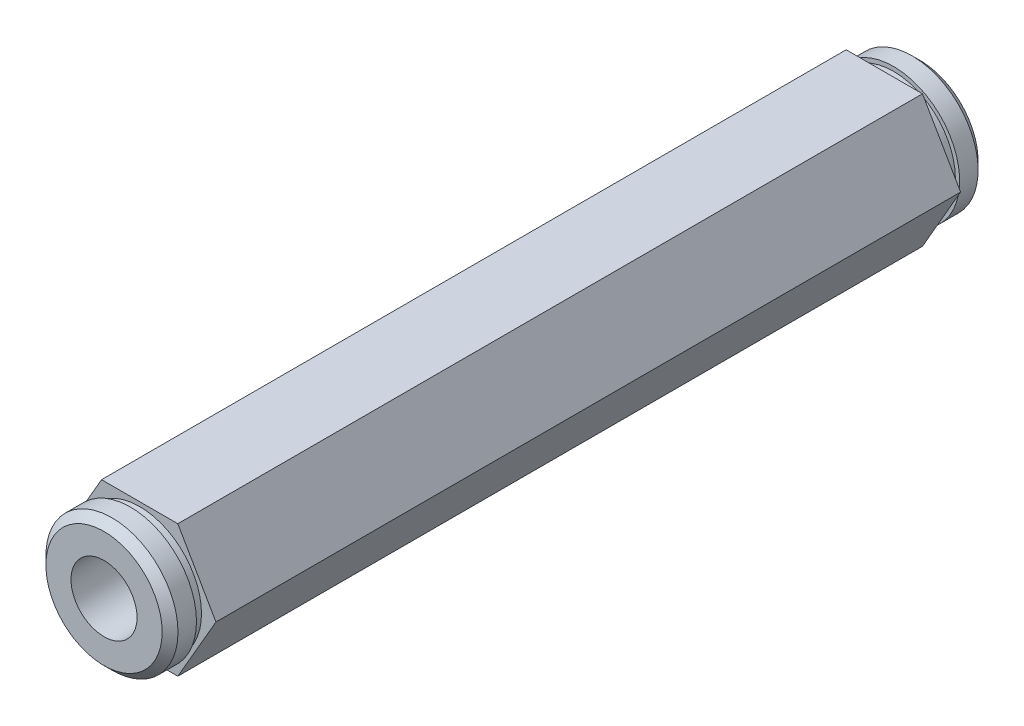
SolidWorks part; units mm, degrees
ref_plane "Front Plane" through (0, 0, 0) normal (0, 0, 1) x (1, 0, 0)
ref_plane "Top Plane" through (0, 0, 0) normal (0, 1, 0) x (1, 0, 0)
ref_plane "Right Plane" through (0, 0, 0) normal (1, 0, 0) x (0, 0, -1)
sketch "Sketch1" plane through (0, 0, 0) normal (0, 0, 1) x (1, 0, 0)
  line L1 (7.3323, 0) -> (3.6662, 6.35)
  line L2 (3.6662, 6.35) -> (-3.6662, 6.35)
  line L3 (-3.6662, 6.35) -> (-7.3323, 0)
  line L4 (-7.3323, 0) -> (-3.6662, -6.35)
  line L5 (-3.6662, -6.35) -> (3.6662, -6.35)
  line L6 (3.6662, -6.35) -> (7.3323, 0)
  circle A0 centre (0, 0) radius 6.35 construction
  dimension "D1" = 12.7
extrude "Boss-Extrude1" add sketch "Sketch1" along normal mid plane 28.575
sketch "Sketch2" plane through (0, 0, -14.2875) normal (0, 0, -1) x (-1, 0, 0)
  circle A0 centre (0, 0) radius 5.9436
  dimension "D1" = 11.8872
extrude "Boss-Extrude2" add sketch "Sketch2" along normal blind 0.889
sketch "Sketch3" plane through (0, 0, -15.1765) normal (0, 0, -1) x (-1, 0, 0)
  circle A0 centre (0, 0) radius 6.35
  dimension "D1" = 12.7
extrude "Boss-Extrude3" add sketch "Sketch3" along normal blind 2.54
chamfer "Chamfer1" distance 0.762 angle 45 1 edges at (-6.35, 0, -17.7165)
sketch "Sketch5" plane through (0, 0, 14.2875) normal (0, 0, 1) x (1, 0, 0)
  line L1 (3.6662, 6.35) -> (-3.6662, 6.35)
  line L2 (-3.6662, 6.35) -> (-7.3323, 0)
  line L3 (-7.3323, 0) -> (-3.6662, -6.35)
  line L4 (-3.6662, -6.35) -> (3.6662, -6.35)
  line L5 (3.6662, -6.35) -> (7.3323, 0)
  line L6 (7.3323, 0) -> (3.6662, 6.35)
  circle A0 centre (0, 0) radius 6.35 construction
  dimension "D1" = 12.7
extrude "Boss-Extrude4" add sketch "Sketch5" along normal blind 43.0149
sketch "Sketch6" plane through (0, 0, 57.3024) normal (0, 0, 1) x (1, 0, 0)
  circle A0 centre (0, 0) radius 5.9436
  dimension "D1" = 11.8872
extrude "Boss-Extrude5" add sketch "Sketch6" along normal blind 0.889
sketch "Sketch7" plane through (0, 0, 58.1914) normal (0, 0, 1) x (1, 0, 0)
  circle A0 centre (0, 0) radius 6.35
  dimension "D1" = 12.7
extrude "Boss-Extrude6" add sketch "Sketch7" along normal blind 2.54
chamfer "Chamfer2" distance 0.762 angle 45 1 edges at (6.35, 0, 60.7314)
hole_wizard "1/4 (0.25) Diameter Hole1" positions "Sketch10" profile "Sketch11" hole size "1/4" standard "ANSI Inch"
sketch "Sketch10" plane through (0, 0, 60.7314) normal (0, 0, 1) x (1, 0, 0)
  point P0 (0, 0)
sketch "Sketch11" plane through (0, 0, 60.7314) normal (1, 0, 0) x (0, -1, 0)
  line L0 (0, 0) -> (0, 8.2577)
  line L1 (0, 8.2577) -> (3.175, 6.35)
  line L2 (3.175, 6.35) -> (3.175, 0)
  line L5 (3.175, 0) -> (0, 0)
  line L10 (0, 8.2577) -> (-3.175, 6.35) construction
  line L11 (0, -6.35) -> (0, 107.95) construction
  dimension "Hole Dia." = 6.35
  dimension "Hole Depth" = 6.35
  dimension "Drill Angle" = 118
